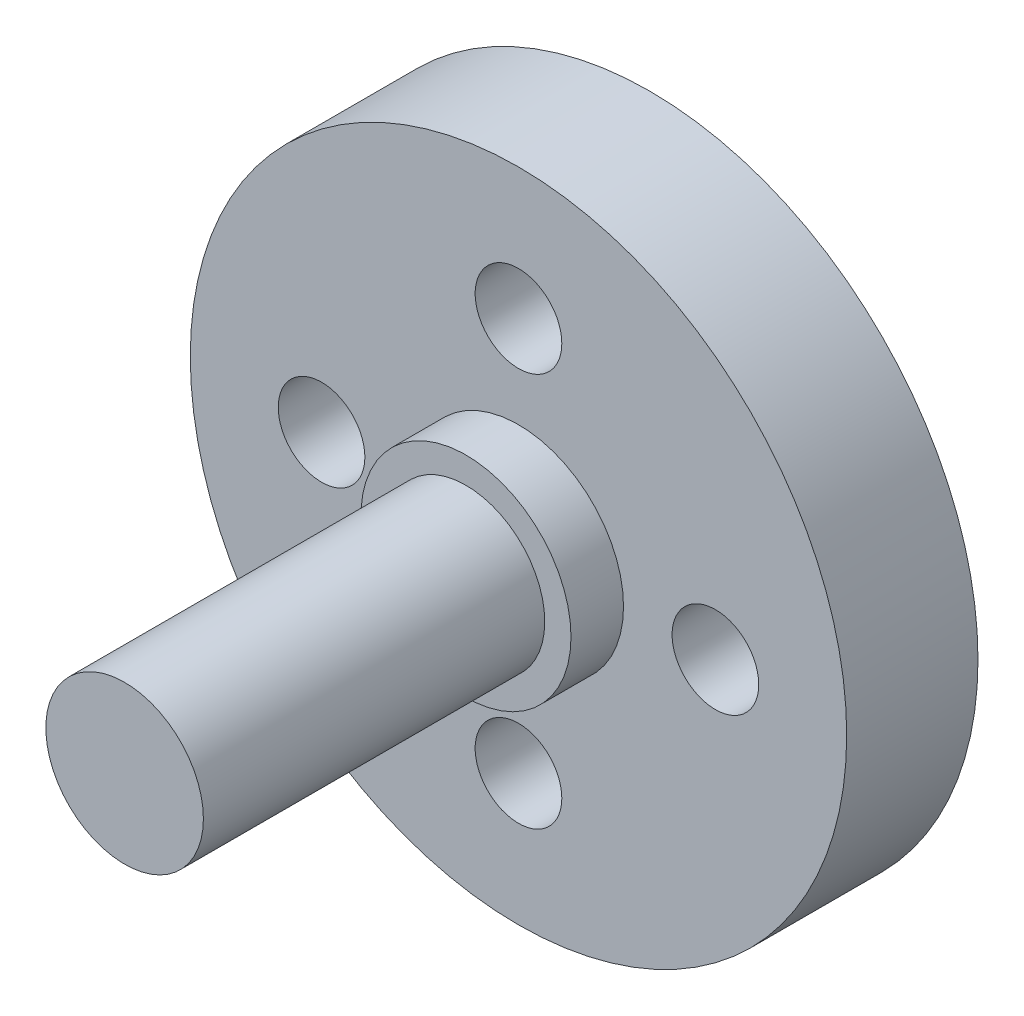
SolidWorks part; units mm, degrees
material "5052-H34"
ref_plane "正面" through (0, 0, 0) normal (0, 0, 1) x (1, 0, 0)
ref_plane "平面" through (0, 0, 0) normal (0, 1, 0) x (1, 0, 0)
ref_plane "右側面" through (0, 0, 0) normal (1, 0, 0) x (0, 0, -1)
sketch "ｽｹｯﾁ1" plane through (0, 0, 0) normal (0, 0, 1) x (1, 0, 0)
  circle A0 centre (0, 0) radius 12.5
  dimension "D1" = 25
extrude "ﾎﾞｽ - 押し出し1" add sketch "ｽｹｯﾁ1" along normal blind 5
sketch "ｽｹｯﾁ2" plane through (0, 0, 5) normal (0, 0, 1) x (1, 0, 0)
  circle A0 centre (0, 0) radius 4
  dimension "D1" = 8
extrude "ﾎﾞｽ - 押し出し2" add sketch "ｽｹｯﾁ2" along normal blind 2
sketch "ｽｹｯﾁ3" plane through (0, 0, 7) normal (0, 0, 1) x (1, 0, 0)
  circle A0 centre (0, 0) radius 3
  dimension "D1" = 6
extrude "ﾎﾞｽ - 押し出し3" add sketch "ｽｹｯﾁ3" along normal blind 13
sketch "ｽｹｯﾁ4" plane through (0, 0, 5) normal (0, 0, 1) x (1, 0, 0)
  line L0 (0, 0) -> (0, 7.5) construction
  circle A0 centre (0, 7.5) radius 1.65
  circle A1 centre (7.5, 0) radius 1.65
  circle A2 centre (0, -7.5) radius 1.65
  circle A3 centre (-7.5, 0) radius 1.65
  point P13 (0, 0)
  dimension "D1" = 3.3
  dimension "D3" = 15
  dimension "D2" = 4
extrude "ｶｯﾄ - 押し出し1" cut sketch "ｽｹｯﾁ4" against normal through all
